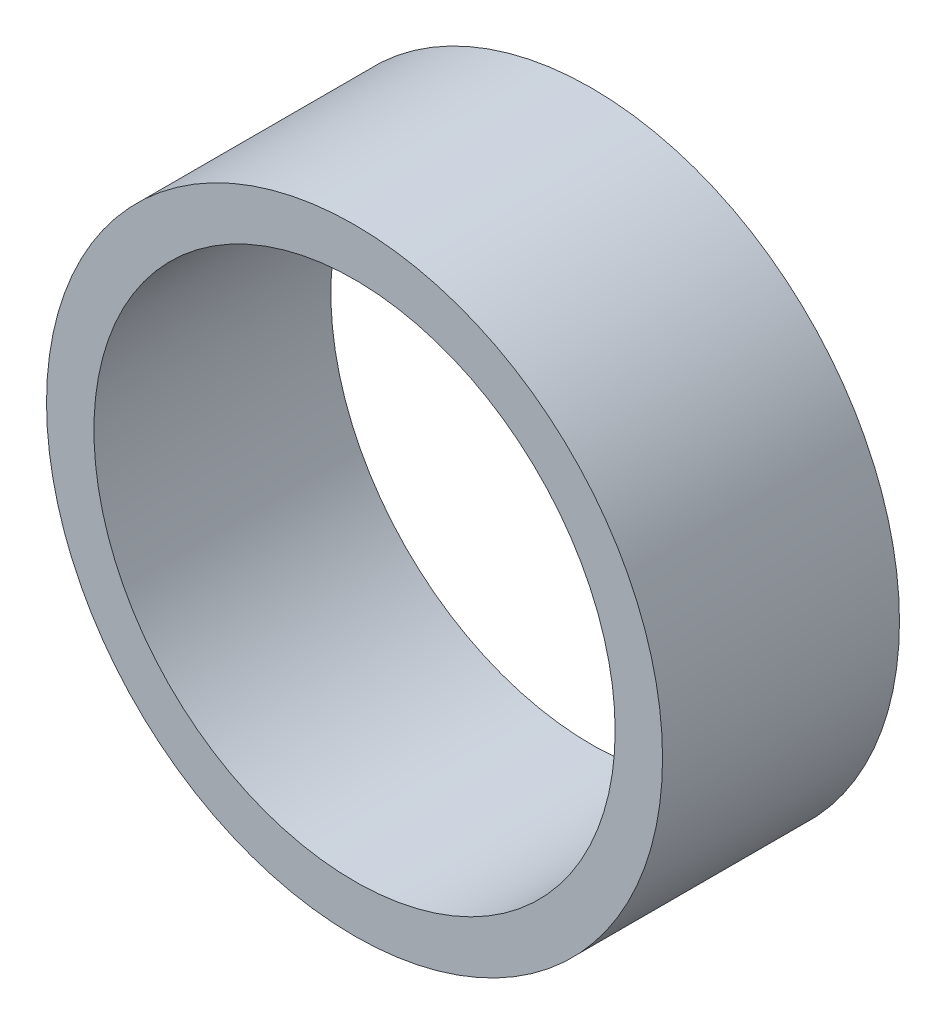
SolidWorks part; units mm, degrees
material "ABS"
ref_plane "Front Plane" through (0, 0, 0) normal (0, 0, 1) x (1, 0, 0)
ref_plane "Top Plane" through (0, 0, 0) normal (0, 1, 0) x (1, 0, 0)
ref_plane "Right Plane" through (0, 0, 0) normal (1, 0, 0) x (0, 0, -1)
sketch "Sketch1" plane through (0, 0, 0) normal (0, 0, 1) x (1, 0, 0)
  circle A0 centre (0, 0) radius 2.794
  circle A1 centre (0, 0) radius 3.302
  dimension "D1" = 5.588
  dimension "D2" = 0.508
extrude "Boss-Extrude1" add sketch "Sketch1" along normal blind 2.54
